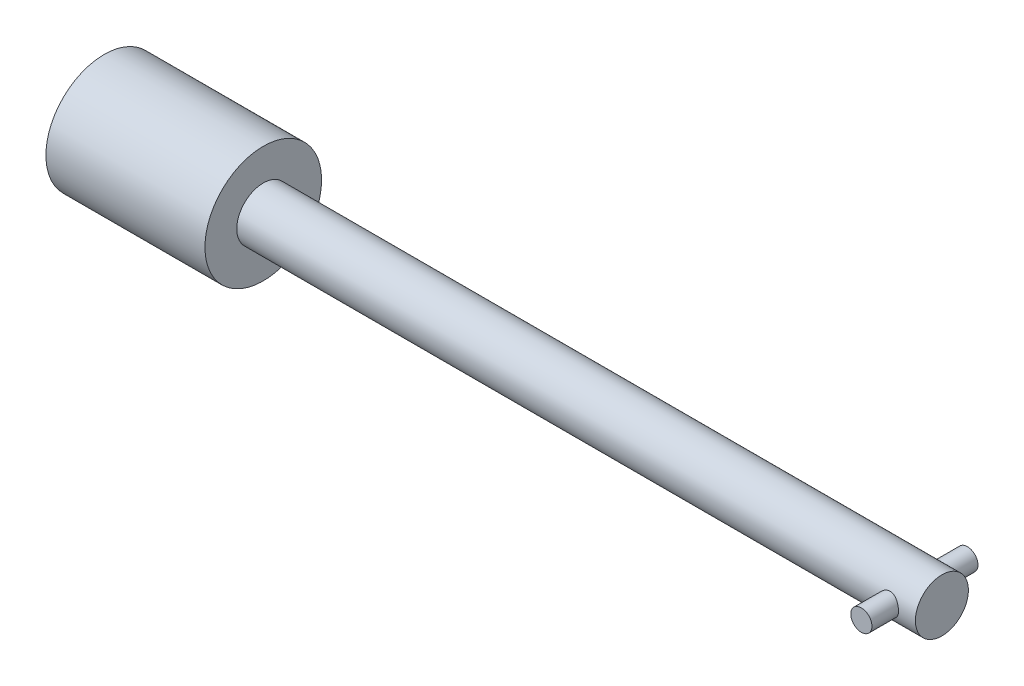
SolidWorks part; units mm, degrees
material "AISI 304"
ref_plane "Front" through (0, 0, 0) normal (0, 0, 1) x (1, 0, 0)
ref_plane "Top" through (0, 0, 0) normal (0, 1, 0) x (1, 0, 0)
ref_plane "Right" through (0, 0, 0) normal (1, 0, 0) x (0, 0, -1)
sketch "Sketch1" plane through (0, 0, 0) normal (1, 0, 0) x (0, 0, -1)
  circle A0 centre (0, 0) radius 5.5
  dimension "D1" = 11
extrude "Boss-Extrude1" add sketch "Sketch1" along normal blind 15
sketch "Sketch2" plane through (15, 0, 0) normal (1, 0, 0) x (0, 0, -1)
  circle A0 centre (0, 0) radius 2.5
  dimension "D1" = 5
extrude "Boss-Extrude2" add sketch "Sketch2" along normal blind 64
sketch "Sketch3" plane through (0, 0, 0) normal (-1, 0, 0) x (0, 0, 1)
  circle A0 centre (0, 0) radius 2.5
  dimension "D1" = 5
extrude "Cut-Extrude1" cut sketch "Sketch3" against normal blind 8
ref_plane "Plane1" through (0, 0, 2.5) normal (0, 0, 1) x (1, 0, 0)
sketch "Sketch4" plane through (0, 0, 2.5) normal (0, 0, 1) x (1, 0, 0)
  circle A0 centre (76.4053, 0) radius 1
  dimension "D1" = 2
extrude "Boss-Extrude3" add sketch "Sketch4" along normal blind 2.5 and the other way blind 7.5
